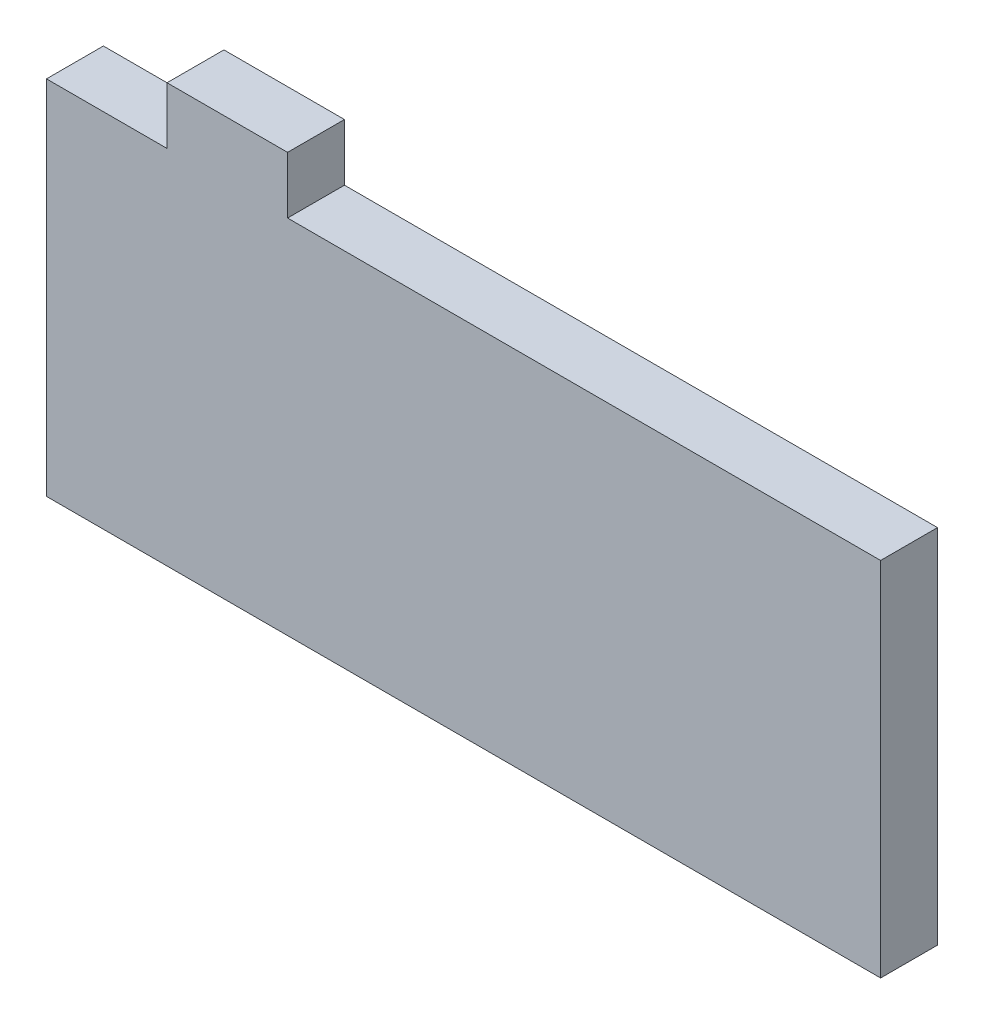
SolidWorks part; units mm, degrees
ref_plane "Front Plane" through (0, 0, 0) normal (0, 0, 1) x (1, 0, 0)
ref_plane "Top Plane" through (0, 0, 0) normal (0, 1, 0) x (1, 0, 0)
ref_plane "Right Plane" through (0, 0, 0) normal (1, 0, 0) x (0, 0, -1)
sketch "Sketch1" plane through (0, 0, 0) normal (0, 0, 1) x (1, 0, 0)
  line L1 (-21.971, -9.525) -> (21.971, -9.525)
  line L2 (-21.971, -9.525) -> (-21.971, 9.525)
  line L3 (-21.971, 9.525) -> (21.971, 9.525)
  line L4 (21.971, -9.525) -> (21.971, 9.525)
  line L5 (-21.971, -9.525) -> (21.971, 9.525) construction
  line L6 (-21.971, 9.525) -> (21.971, -9.525) construction
  point P0 (0, 0)
  dimension "D1" = 19.05
  dimension "D2" = 43.942
extrude "Body" add sketch "Sketch1" along normal blind 2.9972
sketch "Sketch2" plane through (0, 9.525, 0) normal (0, 1, 0) x (1, 0, 0)
  line L0 (21.971, 0) -> (-21.971, 0) construction
  line L1 (-15.621, 0) -> (-9.271, 0)
  line L2 (-15.621, 0) -> (-15.621, -2.9972)
  line L3 (-15.621, -2.9972) -> (-9.271, -2.9972)
  line L4 (-9.271, 0) -> (-9.271, -2.9972)
  line L5 (21.971, -2.9972) -> (-21.971, -2.9972) construction
  line L6 (-21.971, -2.9972) -> (-21.971, 0) construction
  dimension "D1" = 6.35
  dimension "D2" = 6.35
extrude "Tab" add sketch "Sketch2" along normal blind 2.9972
sketch "Sketch3" plane through (0, 0, 2.9972) normal (0, 0, 1) x (1, 0, 0)
  line L0 (-14.859, 12.5222) -> (-14.859, 8.255)
  line L1 (-15.621, 12.5222) -> (-9.271, 12.5222) construction
  line L2 (-14.859, 8.255) -> (-14.224, 8.255)
  line L3 (-14.224, 8.255) -> (-14.224, 12.5222)
  line L4 (-15.621, 9.525) -> (-9.271, 9.525) construction
  line L5 (-12.446, 9.525) -> (-12.446, 12.5222) construction
  line L6 (-14.859, 12.5222) -> (-14.224, 12.5222)
  line L7 (-10.033, 12.5222) -> (-10.668, 12.5222)
  line L8 (-10.668, 8.255) -> (-10.668, 12.5222)
  line L9 (-10.033, 8.255) -> (-10.668, 8.255)
  line L10 (-10.033, 12.5222) -> (-10.033, 8.255)
  line L11 (-8.636, 9.525) -> (-8.636, 8.255)
  line L12 (-15.621, 9.525) -> (-16.256, 9.525)
  line L13 (-15.621, 9.525) -> (-15.621, 8.255)
  line L14 (-15.621, 8.255) -> (-16.256, 8.255)
  line L15 (-16.256, 9.525) -> (-16.256, 8.255)
  line L16 (-9.271, 8.255) -> (-8.636, 8.255)
  line L17 (-9.271, 9.525) -> (-9.271, 8.255)
  line L18 (-9.271, 9.525) -> (-8.636, 9.525)
  line L19 (-15.621, 12.5222) -> (-15.621, 9.525) construction
  dimension "D1" = 0.635
  dimension "D2" = 0.635
  dimension "D3" = 1.27
  dimension "D4" = 0.762
extrude "Slots" [suppressed] cut sketch "Sketch3" against normal through all
fillet "Fillet1" [suppressed] radius 0.254
ref_plane "Tab Midplane" [suppressed] through (-12.7, 0, 0) normal (-1, 0, 0) x (0, 0, 1)
ref_plane "Body Horizontal Midplane" through (0, 0, 0) normal (0, 1, 0) x (1, 0, 0)
ref_plane "Body Vertical Midplane" through (0, 0, 0) normal (-1, 0, 0) x (0, 0, 1)
